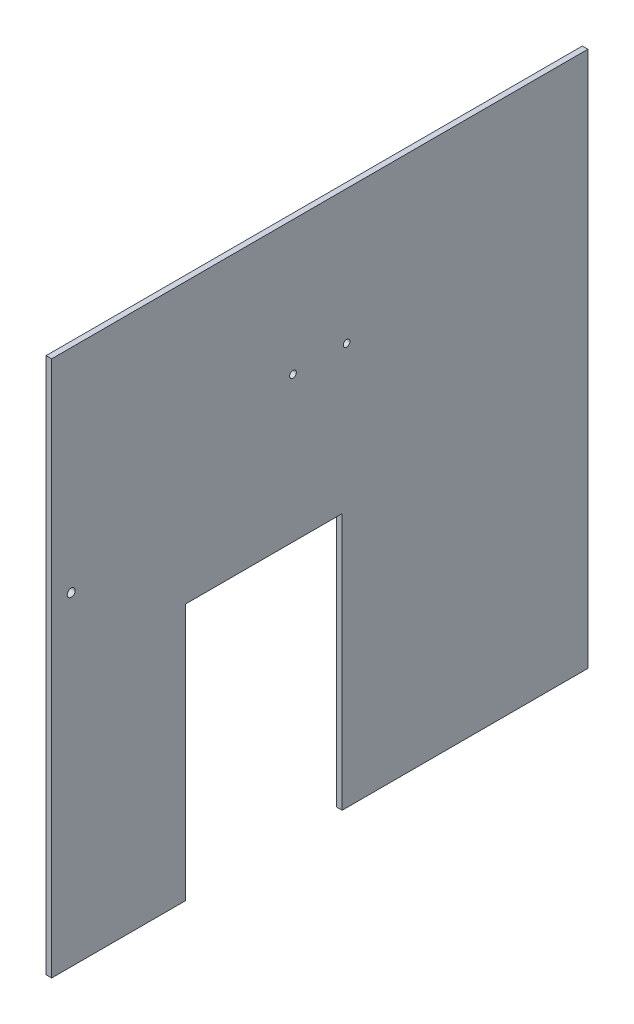
SolidWorks part; units mm, degrees
ref_plane "Front Plane" through (0, 0, 0) normal (0, 0, 1) x (1, 0, 0)
ref_plane "Top Plane" through (0, 0, 0) normal (0, 1, 0) x (1, 0, 0)
ref_plane "Right Plane" through (0, 0, 0) normal (1, 0, 0) x (0, 0, -1)
sketch "Sketch1" plane through (0, 0, 0) normal (1, 0, 0) x (0, 0, -1)
  line L1 (-152.4, 152.4) -> (152.4, 152.4)
  line L2 (-152.4, 152.4) -> (-152.4, -152.4)
  line L3 (-152.4, -152.4) -> (152.4, -152.4)
  line L4 (152.4, 152.4) -> (152.4, -152.4)
  line L5 (-152.4, 152.4) -> (152.4, -152.4) construction
  line L6 (-152.4, -152.4) -> (152.4, 152.4) construction
  line L7 (-76.2, -152.4) -> (12.7, -152.4)
  line L8 (-76.2, -152.4) -> (-76.2, -6.35)
  line L9 (-76.2, -6.35) -> (12.7, -6.35)
  line L10 (12.7, -152.4) -> (12.7, -6.35)
  point P0 (0, 0)
  dimension "D1" = 304.8
  dimension "D2" = 304.8
  dimension "D3" = 76.2
  dimension "D4" = 88.9
  dimension "D5" = 146.05
extrude "Boss-Extrude1" add sketch "Sketch1" along normal blind 3.175 contours L10 L3 L4 L1 L2 L8 L9
sketch "Sketch2" plane through (3.175, 0, 0) normal (1, 0, 0) x (0, 0, -1)
  line L0 (-152.4, 152.4) -> (-152.4, -152.4) construction
  line L1 (-152.4, -152.4) -> (-76.2, -152.4) construction
  circle A0 centre (-141.2875, 31.75) radius 2.286
  dimension "D2" = 4.572
  dimension "D1" = 11.1125
  dimension "D3" = 184.15
extrude "Cut-Extrude1" cut sketch "Sketch2" against normal through all
hole_wizard "#6 (0.15) Diameter Hole1" positions "Sketch3" profile "Sketch4" hole size "#6" standard "ANSI Inch" end condition through all
sketch "Sketch3" plane through (3.175, 0, 0) normal (1, 0, 0) x (0, 0, -1)
  line L0 (-152.4, 152.4) -> (152.4, 152.4) construction
  line L1 (-152.4, 152.4) -> (-152.4, -152.4) construction
  point P0 (-15.24, 76.2)
  point P2 (15.24, 76.2)
  point P7 (0, 0)
  point P8 (0, 0)
  point P9 (0, 0)
  point P10 (0, 0)
  point P13 (0, 0)
  dimension "D1" = 76.2
  dimension "D2" = 76.2
  dimension "D3" = 30.48
  dimension "D4" = 137.16
sketch "Sketch4" plane through (3.175, 76.2, 15.24) normal (0, 1, 0) x (0, 0, -1)
  line L0 (0, 0) -> (0, 3.175)
  line L1 (0, 3.175) -> (1.905, 3.175)
  line L2 (1.905, 3.175) -> (1.905, 0)
  line L5 (1.905, 0) -> (0, 0)
  line L11 (0, -6.35) -> (0, 107.95) construction
  dimension "Thru Hole Dia." = 3.81
  dimension "Thru Hole Depth" = 3.175
